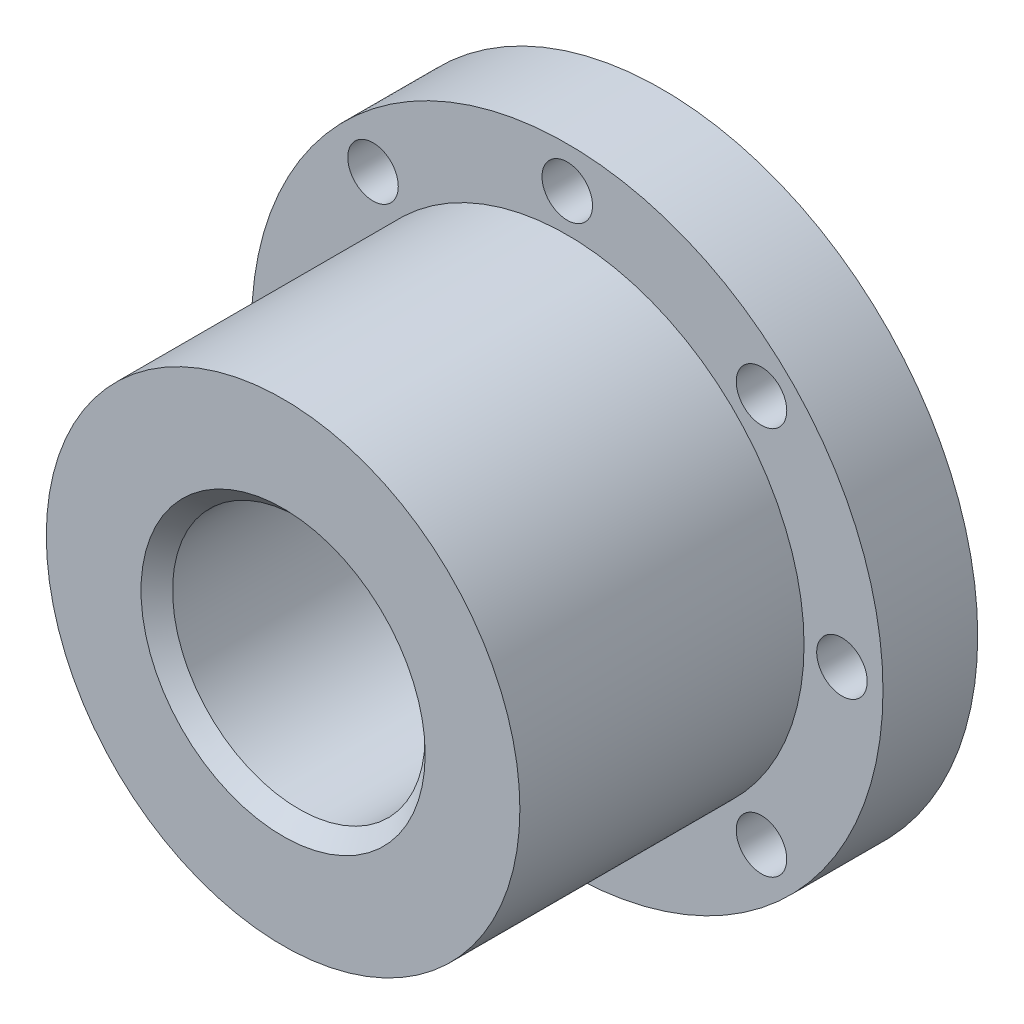
SolidWorks part; units mm, degrees
ref_plane "前视基准面" through (0, 0, 0) normal (0, 0, 1) x (1, 0, 0)
ref_plane "上视基准面" through (0, 0, 0) normal (0, 1, 0) x (1, 0, 0)
ref_plane "右视基准面" through (0, 0, 0) normal (1, 0, 0) x (0, 0, -1)
sketch "草图1" plane through (0, 0, 0) normal (0, 0, 1) x (1, 0, 0)
  circle A0 centre (0, 0) radius 100
extrude "凸台-拉伸1" add sketch "草图1" along normal blind 30
sketch "草图2" plane through (0, 0, 0) normal (0, 0, 1) x (1, 0, 0)
  circle A0 centre (0, 0) radius 75
extrude "凸台-拉伸2" add sketch "草图2" along normal blind 120
sketch "草图3" plane through (0, 0, 0) normal (0, 0, 1) x (1, 0, 0)
  circle A0 centre (0, 0) radius 40
extrude "切除-拉伸1" cut sketch "草图3" along normal through all
sketch "草图4" plane through (0, 0, 0) normal (0, 0, 1) x (1, 0, 0)
  line L0 (-108.75, 0) -> (108.75, 0) construction
  line L1 (0, -108.75) -> (0, 108.75) construction
  circle A0 centre (87, 0) radius 8
  circle A1 centre (61.5183, 61.5183) radius 8
  circle A2 centre (0, 87) radius 8
  circle A3 centre (-61.5183, 61.5183) radius 8
  circle A4 centre (-87, 0) radius 8
  circle A5 centre (-61.5183, -61.5183) radius 8
  circle A6 centre (0, -87) radius 8
  circle A7 centre (61.5183, -61.5183) radius 8
extrude "切除-拉伸2" cut sketch "草图4" along normal through all
chamfer "倒角1" distance 5 angle 45 1 edges at (40, 0, 120)
